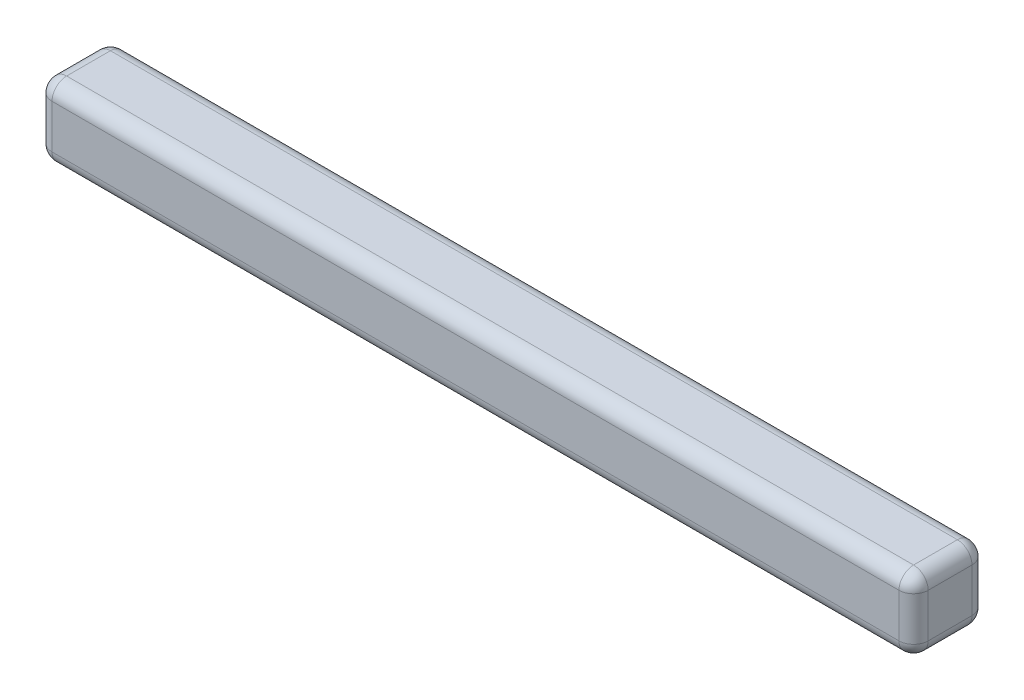
SolidWorks part; units mm, degrees
ref_plane "Front Plane" through (0, 0, 0) normal (0, 0, 1) x (1, 0, 0)
ref_plane "Top Plane" through (0, 0, 0) normal (0, 1, 0) x (1, 0, 0)
ref_plane "Right Plane" through (0, 0, 0) normal (1, 0, 0) x (0, 0, -1)
sketch "Sketch1" plane through (0, 0, 0) normal (0, 1, 0) x (1, 0, 0)
  line L1 (-30, 2.5) -> (30, 2.5)
  line L2 (-30, 2.5) -> (-30, -2.5)
  line L3 (-30, -2.5) -> (30, -2.5)
  line L4 (30, 2.5) -> (30, -2.5)
  line L5 (-30, 2.5) -> (30, -2.5) construction
  line L6 (-30, -2.5) -> (30, 2.5) construction
  point P0 (0, 0)
  dimension "D1" = 5
  dimension "D2" = 60
extrude "Boss-Extrude1" add sketch "Sketch1" along normal blind 5
fillet "Fillet1" radius 1 12 edges at (30, 2.5, 2.5) (30, 2.5, -2.5) (-30, 2.5, -2.5) (-30, 2.5, 2.5) (0, 0, -2.5) (-30, 0, 0) (0, 0, 2.5) (30, 0, 0) (0, 5, 2.5) (-30, 5, 0) (0, 5, -2.5) (30, 5, 0)
